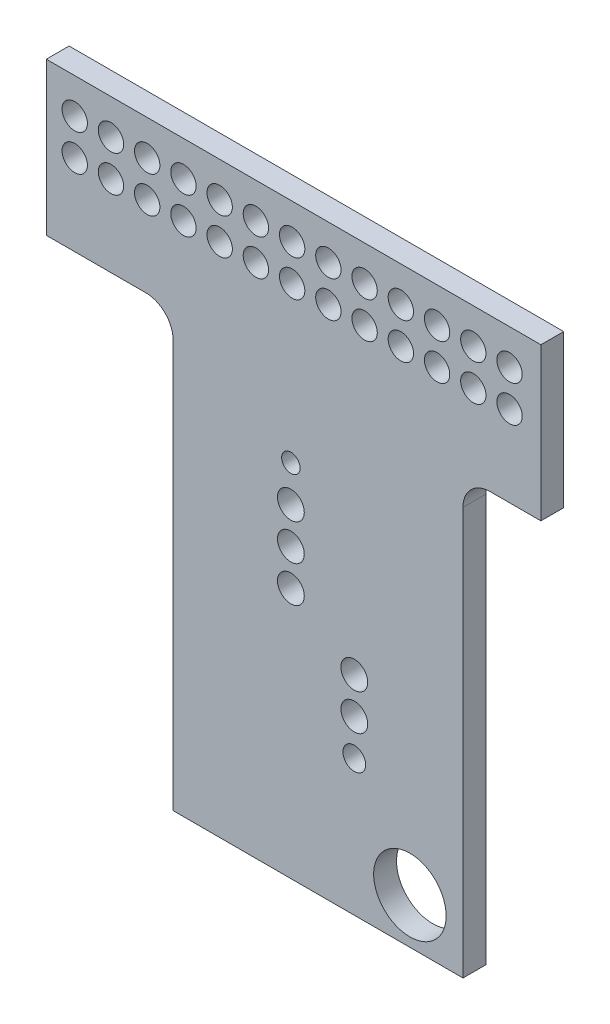
SolidWorks part; units mm, degrees
ref_plane "Front Plane" through (0, 0, 0) normal (0, 0, 1) x (1, 0, 0)
ref_plane "Top Plane" through (0, 0, 0) normal (0, 1, 0) x (1, 0, 0)
ref_plane "Right Plane" through (0, 0, 0) normal (1, 0, 0) x (0, 0, -1)
sketch "Model" plane through (0, 0, 0) normal (0, 0, 1) x (1, 0, 0)
  line L0 (17.145, 24.3014) -> (17.145, 26.1811) construction
  line L1 (21.59, 10.4648) -> (21.59, 8.5852) construction
  line L8 (22.5298, 8.5852) -> (22.5298, 10.4648) construction
  line L9 (22.5298, 10.4648) -> (20.6502, 10.4648) construction
  line L10 (20.6502, 10.4648) -> (20.6502, 8.5852) construction
  line L11 (20.6502, 8.5852) -> (22.5298, 8.5852) construction
  line L12 (22.5298, 8.5852) -> (22.5298, 10.4648) construction
  line L13 (22.5298, 10.4648) -> (20.6502, 10.4648) construction
  line L14 (20.6502, 10.4648) -> (20.6502, 8.5852) construction
  line L15 (20.6502, 8.5852) -> (22.5298, 8.5852) construction
  line L16 (16.2052, 26.1811) -> (16.2052, 24.3014) construction
  line L17 (16.2052, 24.3014) -> (18.0848, 24.3014) construction
  line L18 (18.0848, 24.3014) -> (18.0848, 26.1811) construction
  line L19 (18.0848, 26.1811) -> (16.2052, 26.1811) construction
  line L20 (16.2052, 26.1811) -> (16.2052, 24.3014) construction
  line L21 (16.2052, 24.3014) -> (18.0848, 24.3014) construction
  line L22 (18.0848, 24.3014) -> (18.0848, 26.1811) construction
  line L23 (18.0848, 26.1811) -> (16.2052, 26.1811) construction
  line L24 (8.89, 0) -> (29.21, 0)
  line L25 (34.671, 41.1734) -> (0, 41.1734)
  line L26 (0, 41.1734) -> (0, 30.48)
  line L27 (0, 30.48) -> (6.985, 30.48)
  line L28 (8.89, 28.575) -> (8.89, 0)
  line L29 (29.21, 28.575) -> (29.21, 0)
  line L30 (34.671, 30.48) -> (34.671, 41.1734)
  line L31 (34.671, 30.48) -> (31.115, 30.48)
  circle A0 centre (17.145, 25.2413) radius 0.6465
  circle A1 centre (21.59, 9.525) radius 0.7974
  arc A2 (8.89, 28.575) -> (6.985, 30.48) centre (6.985, 28.575) ccw
  arc A3 (31.115, 30.48) -> (29.21, 28.575) centre (31.115, 28.575) ccw
  circle A4 centre (1.9939, 38.7096) radius 0.127
  circle A5 centre (1.9939, 36.1696) radius 0.127
  circle A6 centre (4.5339, 38.7096) radius 0.127
  circle A7 centre (4.5339, 36.1696) radius 0.127
  circle A8 centre (7.0739, 38.7096) radius 0.127
  circle A9 centre (7.0739, 36.1696) radius 0.127
  circle A10 centre (9.6139, 38.7096) radius 0.127
  circle A11 centre (9.6139, 36.1696) radius 0.127
  circle A12 centre (12.1539, 38.7096) radius 0.127
  circle A13 centre (12.1539, 36.1696) radius 0.127
  circle A14 centre (1.9939, 38.7096) radius 0.889
  circle A15 centre (1.9939, 36.1696) radius 0.889
  circle A16 centre (4.5339, 36.1696) radius 0.889
  circle A17 centre (7.0739, 36.1696) radius 0.889
  circle A18 centre (9.6139, 36.1696) radius 0.889
  circle A19 centre (12.1539, 36.1696) radius 0.889
  circle A20 centre (4.5339, 38.7096) radius 0.889
  circle A21 centre (7.0739, 38.7096) radius 0.889
  circle A22 centre (9.6139, 38.7096) radius 0.889
  circle A23 centre (12.1539, 38.7096) radius 0.889
  circle A24 centre (14.6939, 38.7096) radius 0.127
  circle A25 centre (14.6939, 36.1696) radius 0.127
  circle A26 centre (17.2339, 38.7096) radius 0.127
  circle A27 centre (17.2339, 36.1696) radius 0.127
  circle A28 centre (19.7739, 38.7096) radius 0.127
  circle A29 centre (19.7739, 36.1696) radius 0.127
  circle A30 centre (22.3139, 38.7096) radius 0.127
  circle A31 centre (22.3139, 36.1696) radius 0.127
  circle A32 centre (24.8539, 38.7096) radius 0.127
  circle A33 centre (24.8539, 36.1696) radius 0.127
  circle A34 centre (14.6939, 38.7096) radius 0.889
  circle A35 centre (14.6939, 36.1696) radius 0.889
  circle A36 centre (17.2339, 36.1696) radius 0.889
  circle A37 centre (19.7739, 36.1696) radius 0.889
  circle A38 centre (22.3139, 36.1696) radius 0.889
  circle A39 centre (24.8539, 36.1696) radius 0.889
  circle A40 centre (17.2339, 38.7096) radius 0.889
  circle A41 centre (19.7739, 38.7096) radius 0.889
  circle A42 centre (22.3139, 38.7096) radius 0.889
  circle A43 centre (24.8539, 38.7096) radius 0.889
  circle A44 centre (27.3939, 38.7096) radius 0.127
  circle A45 centre (27.3939, 36.1696) radius 0.127
  circle A46 centre (29.9339, 38.7096) radius 0.127
  circle A47 centre (29.9339, 36.1696) radius 0.127
  circle A48 centre (32.4739, 38.7096) radius 0.127
  circle A49 centre (32.4739, 36.1696) radius 0.127
  circle A50 centre (27.3939, 38.7096) radius 0.889
  circle A51 centre (27.3939, 36.1696) radius 0.889
  circle A52 centre (29.9339, 36.1696) radius 0.889
  circle A53 centre (32.4739, 36.1696) radius 0.889
  circle A54 centre (29.9339, 38.7096) radius 0.889
  circle A55 centre (32.4739, 38.7096) radius 0.889
  circle B0 centre (1.9939, 36.1696) radius 0.6858
  circle B1 centre (1.9939, 36.1696) radius 0.6858
  line B2 (1.3081, 38.4255) -> (1.3081, 38.9937)
  line B3 (1.3081, 38.9937) -> (1.7098, 39.3954)
  line B4 (1.7098, 39.3954) -> (2.278, 39.3954)
  line B5 (2.278, 39.3954) -> (2.6797, 38.9937)
  line B6 (2.6797, 38.9937) -> (2.6797, 38.4255)
  line B7 (2.6797, 38.4255) -> (2.278, 38.0238)
  line B8 (2.278, 38.0238) -> (1.7098, 38.0238)
  line B9 (1.7098, 38.0238) -> (1.3081, 38.4255)
  line B10 (1.3081, 38.4255) -> (1.3081, 38.9937)
  line B11 (1.3081, 38.9937) -> (1.7098, 39.3954)
  line B12 (1.7098, 39.3954) -> (2.278, 39.3954)
  line B13 (2.278, 39.3954) -> (2.6797, 38.9937)
  line B14 (2.6797, 38.9937) -> (2.6797, 38.4255)
  line B15 (2.6797, 38.4255) -> (2.278, 38.0238)
  line B16 (2.278, 38.0238) -> (1.7098, 38.0238)
  line B17 (1.7098, 38.0238) -> (1.3081, 38.4255)
  line B18 (3.8481, 35.8855) -> (3.8481, 36.4537)
  line B19 (3.8481, 36.4537) -> (4.2498, 36.8554)
  line B20 (4.2498, 36.8554) -> (4.818, 36.8554)
  line B21 (4.818, 36.8554) -> (5.2197, 36.4537)
  line B22 (5.2197, 36.4537) -> (5.2197, 35.8855)
  line B23 (5.2197, 35.8855) -> (4.818, 35.4838)
  line B24 (4.818, 35.4838) -> (4.2498, 35.4838)
  line B25 (4.2498, 35.4838) -> (3.8481, 35.8855)
  line B26 (3.8481, 35.8855) -> (3.8481, 36.4537)
  line B27 (3.8481, 36.4537) -> (4.2498, 36.8554)
  line B28 (4.2498, 36.8554) -> (4.818, 36.8554)
  line B29 (4.818, 36.8554) -> (5.2197, 36.4537)
  line B30 (5.2197, 36.4537) -> (5.2197, 35.8855)
  line B31 (5.2197, 35.8855) -> (4.818, 35.4838)
  line B32 (4.818, 35.4838) -> (4.2498, 35.4838)
  line B33 (4.2498, 35.4838) -> (3.8481, 35.8855)
  line B34 (3.8481, 38.4255) -> (3.8481, 38.9937)
  line B35 (3.8481, 38.9937) -> (4.2498, 39.3954)
  line B36 (4.2498, 39.3954) -> (4.818, 39.3954)
  line B37 (4.818, 39.3954) -> (5.2197, 38.9937)
  line B38 (5.2197, 38.9937) -> (5.2197, 38.4255)
  line B39 (5.2197, 38.4255) -> (4.818, 38.0238)
  line B40 (4.818, 38.0238) -> (4.2498, 38.0238)
  line B41 (4.2498, 38.0238) -> (3.8481, 38.4255)
  line B42 (3.8481, 38.4255) -> (3.8481, 38.9937)
  line B43 (3.8481, 38.9937) -> (4.2498, 39.3954)
  line B44 (4.2498, 39.3954) -> (4.818, 39.3954)
  line B45 (4.818, 39.3954) -> (5.2197, 38.9937)
  line B46 (5.2197, 38.9937) -> (5.2197, 38.4255)
  line B47 (5.2197, 38.4255) -> (4.818, 38.0238)
  line B48 (4.818, 38.0238) -> (4.2498, 38.0238)
  line B49 (4.2498, 38.0238) -> (3.8481, 38.4255)
  line B50 (6.3881, 35.8855) -> (6.3881, 36.4537)
  line B51 (6.3881, 36.4537) -> (6.7898, 36.8554)
  line B52 (6.7898, 36.8554) -> (7.358, 36.8554)
  line B53 (7.358, 36.8554) -> (7.7597, 36.4537)
  line B54 (7.7597, 36.4537) -> (7.7597, 35.8855)
  line B55 (7.7597, 35.8855) -> (7.358, 35.4838)
  line B56 (7.358, 35.4838) -> (6.7898, 35.4838)
  line B57 (6.7898, 35.4838) -> (6.3881, 35.8855)
  line B58 (6.3881, 35.8855) -> (6.3881, 36.4537)
  line B59 (6.3881, 36.4537) -> (6.7898, 36.8554)
  line B60 (6.7898, 36.8554) -> (7.358, 36.8554)
  line B61 (7.358, 36.8554) -> (7.7597, 36.4537)
  line B62 (7.7597, 36.4537) -> (7.7597, 35.8855)
  line B63 (7.7597, 35.8855) -> (7.358, 35.4838)
  line B64 (7.358, 35.4838) -> (6.7898, 35.4838)
  line B65 (6.7898, 35.4838) -> (6.3881, 35.8855)
  line B66 (6.3881, 38.4255) -> (6.3881, 38.9937)
  line B67 (6.3881, 38.9937) -> (6.7898, 39.3954)
  line B68 (6.7898, 39.3954) -> (7.358, 39.3954)
  line B69 (7.358, 39.3954) -> (7.7597, 38.9937)
  line B70 (7.7597, 38.9937) -> (7.7597, 38.4255)
  line B71 (7.7597, 38.4255) -> (7.358, 38.0238)
  line B72 (7.358, 38.0238) -> (6.7898, 38.0238)
  line B73 (6.7898, 38.0238) -> (6.3881, 38.4255)
  line B74 (6.3881, 38.4255) -> (6.3881, 38.9937)
  line B75 (6.3881, 38.9937) -> (6.7898, 39.3954)
  line B76 (6.7898, 39.3954) -> (7.358, 39.3954)
  line B77 (7.358, 39.3954) -> (7.7597, 38.9937)
  line B78 (7.7597, 38.9937) -> (7.7597, 38.4255)
  line B79 (7.7597, 38.4255) -> (7.358, 38.0238)
  line B80 (7.358, 38.0238) -> (6.7898, 38.0238)
  line B81 (6.7898, 38.0238) -> (6.3881, 38.4255)
  line B82 (8.9281, 35.8855) -> (8.9281, 36.4537)
  line B83 (8.9281, 36.4537) -> (9.3298, 36.8554)
  line B84 (9.3298, 36.8554) -> (9.898, 36.8554)
  line B85 (9.898, 36.8554) -> (10.2997, 36.4537)
  line B86 (10.2997, 36.4537) -> (10.2997, 35.8855)
  line B87 (10.2997, 35.8855) -> (9.898, 35.4838)
  line B88 (9.898, 35.4838) -> (9.3298, 35.4838)
  line B89 (9.3298, 35.4838) -> (8.9281, 35.8855)
  line B90 (8.9281, 35.8855) -> (8.9281, 36.4537)
  line B91 (8.9281, 36.4537) -> (9.3298, 36.8554)
  line B92 (9.3298, 36.8554) -> (9.898, 36.8554)
  line B93 (9.898, 36.8554) -> (10.2997, 36.4537)
  line B94 (10.2997, 36.4537) -> (10.2997, 35.8855)
  line B95 (10.2997, 35.8855) -> (9.898, 35.4838)
  line B96 (9.898, 35.4838) -> (9.3298, 35.4838)
  line B97 (9.3298, 35.4838) -> (8.9281, 35.8855)
  line B98 (8.9281, 38.4255) -> (8.9281, 38.9937)
  line B99 (8.9281, 38.9937) -> (9.3298, 39.3954)
  line B100 (9.3298, 39.3954) -> (9.898, 39.3954)
  line B101 (9.898, 39.3954) -> (10.2997, 38.9937)
  line B102 (10.2997, 38.9937) -> (10.2997, 38.4255)
  line B103 (10.2997, 38.4255) -> (9.898, 38.0238)
  line B104 (9.898, 38.0238) -> (9.3298, 38.0238)
  line B105 (9.3298, 38.0238) -> (8.9281, 38.4255)
  line B106 (8.9281, 38.4255) -> (8.9281, 38.9937)
  line B107 (8.9281, 38.9937) -> (9.3298, 39.3954)
  line B108 (9.3298, 39.3954) -> (9.898, 39.3954)
  line B109 (9.898, 39.3954) -> (10.2997, 38.9937)
  line B110 (10.2997, 38.9937) -> (10.2997, 38.4255)
  line B111 (10.2997, 38.4255) -> (9.898, 38.0238)
  line B112 (9.898, 38.0238) -> (9.3298, 38.0238)
  line B113 (9.3298, 38.0238) -> (8.9281, 38.4255)
  line B114 (11.4681, 35.8855) -> (11.4681, 36.4537)
  line B115 (11.4681, 36.4537) -> (11.8698, 36.8554)
  line B116 (11.8698, 36.8554) -> (12.438, 36.8554)
  line B117 (12.438, 36.8554) -> (12.8397, 36.4537)
  line B118 (12.8397, 36.4537) -> (12.8397, 35.8855)
  line B119 (12.8397, 35.8855) -> (12.438, 35.4838)
  line B120 (12.438, 35.4838) -> (11.8698, 35.4838)
  line B121 (11.8698, 35.4838) -> (11.4681, 35.8855)
  line B122 (11.4681, 35.8855) -> (11.4681, 36.4537)
  line B123 (11.4681, 36.4537) -> (11.8698, 36.8554)
  line B124 (11.8698, 36.8554) -> (12.438, 36.8554)
  line B125 (12.438, 36.8554) -> (12.8397, 36.4537)
  line B126 (12.8397, 36.4537) -> (12.8397, 35.8855)
  line B127 (12.8397, 35.8855) -> (12.438, 35.4838)
  line B128 (12.438, 35.4838) -> (11.8698, 35.4838)
  line B129 (11.8698, 35.4838) -> (11.4681, 35.8855)
  line B130 (11.4681, 38.4255) -> (11.4681, 38.9937)
  line B131 (11.4681, 38.9937) -> (11.8698, 39.3954)
  line B132 (11.8698, 39.3954) -> (12.438, 39.3954)
  line B133 (12.438, 39.3954) -> (12.8397, 38.9937)
  line B134 (12.8397, 38.9937) -> (12.8397, 38.4255)
  line B135 (12.8397, 38.4255) -> (12.438, 38.0238)
  line B136 (12.438, 38.0238) -> (11.8698, 38.0238)
  line B137 (11.8698, 38.0238) -> (11.4681, 38.4255)
  line B138 (11.4681, 38.4255) -> (11.4681, 38.9937)
  line B139 (11.4681, 38.9937) -> (11.8698, 39.3954)
  line B140 (11.8698, 39.3954) -> (12.438, 39.3954)
  line B141 (12.438, 39.3954) -> (12.8397, 38.9937)
  line B142 (12.8397, 38.9937) -> (12.8397, 38.4255)
  line B143 (12.8397, 38.4255) -> (12.438, 38.0238)
  line B144 (12.438, 38.0238) -> (11.8698, 38.0238)
  line B145 (11.8698, 38.0238) -> (11.4681, 38.4255)
  line B146 (14.0081, 35.8855) -> (14.0081, 36.4537)
  line B147 (14.0081, 36.4537) -> (14.4098, 36.8554)
  line B148 (14.4098, 36.8554) -> (14.978, 36.8554)
  line B149 (14.978, 36.8554) -> (15.3797, 36.4537)
  line B150 (15.3797, 36.4537) -> (15.3797, 35.8855)
  line B151 (15.3797, 35.8855) -> (14.978, 35.4838)
  line B152 (14.978, 35.4838) -> (14.4098, 35.4838)
  line B153 (14.4098, 35.4838) -> (14.0081, 35.8855)
  line B154 (14.0081, 35.8855) -> (14.0081, 36.4537)
  line B155 (14.0081, 36.4537) -> (14.4098, 36.8554)
  line B156 (14.4098, 36.8554) -> (14.978, 36.8554)
  line B157 (14.978, 36.8554) -> (15.3797, 36.4537)
  line B158 (15.3797, 36.4537) -> (15.3797, 35.8855)
  line B159 (15.3797, 35.8855) -> (14.978, 35.4838)
  line B160 (14.978, 35.4838) -> (14.4098, 35.4838)
  line B161 (14.4098, 35.4838) -> (14.0081, 35.8855)
  line B162 (14.0081, 38.4255) -> (14.0081, 38.9937)
  line B163 (14.0081, 38.9937) -> (14.4098, 39.3954)
  line B164 (14.4098, 39.3954) -> (14.978, 39.3954)
  line B165 (14.978, 39.3954) -> (15.3797, 38.9937)
  line B166 (15.3797, 38.9937) -> (15.3797, 38.4255)
  line B167 (15.3797, 38.4255) -> (14.978, 38.0238)
  line B168 (14.978, 38.0238) -> (14.4098, 38.0238)
  line B169 (14.4098, 38.0238) -> (14.0081, 38.4255)
  line B170 (14.0081, 38.4255) -> (14.0081, 38.9937)
  line B171 (14.0081, 38.9937) -> (14.4098, 39.3954)
  line B172 (14.4098, 39.3954) -> (14.978, 39.3954)
  line B173 (14.978, 39.3954) -> (15.3797, 38.9937)
  line B174 (15.3797, 38.9937) -> (15.3797, 38.4255)
  line B175 (15.3797, 38.4255) -> (14.978, 38.0238)
  line B176 (14.978, 38.0238) -> (14.4098, 38.0238)
  line B177 (14.4098, 38.0238) -> (14.0081, 38.4255)
  line B178 (16.5481, 35.8855) -> (16.5481, 36.4537)
  line B179 (16.5481, 36.4537) -> (16.9498, 36.8554)
  line B180 (16.9498, 36.8554) -> (17.518, 36.8554)
  line B181 (17.518, 36.8554) -> (17.9197, 36.4537)
  line B182 (17.9197, 36.4537) -> (17.9197, 35.8855)
  line B183 (17.9197, 35.8855) -> (17.518, 35.4838)
  line B184 (17.518, 35.4838) -> (16.9498, 35.4838)
  line B185 (16.9498, 35.4838) -> (16.5481, 35.8855)
  line B186 (16.5481, 35.8855) -> (16.5481, 36.4537)
  line B187 (16.5481, 36.4537) -> (16.9498, 36.8554)
  line B188 (16.9498, 36.8554) -> (17.518, 36.8554)
  line B189 (17.518, 36.8554) -> (17.9197, 36.4537)
  line B190 (17.9197, 36.4537) -> (17.9197, 35.8855)
  line B191 (17.9197, 35.8855) -> (17.518, 35.4838)
  line B192 (17.518, 35.4838) -> (16.9498, 35.4838)
  line B193 (16.9498, 35.4838) -> (16.5481, 35.8855)
  line B194 (16.5481, 38.4255) -> (16.5481, 38.9937)
  line B195 (16.5481, 38.9937) -> (16.9498, 39.3954)
  line B196 (16.9498, 39.3954) -> (17.518, 39.3954)
  line B197 (17.518, 39.3954) -> (17.9197, 38.9937)
  line B198 (17.9197, 38.9937) -> (17.9197, 38.4255)
  line B199 (17.9197, 38.4255) -> (17.518, 38.0238)
  line B200 (17.518, 38.0238) -> (16.9498, 38.0238)
  line B201 (16.9498, 38.0238) -> (16.5481, 38.4255)
  line B202 (16.5481, 38.4255) -> (16.5481, 38.9937)
  line B203 (16.5481, 38.9937) -> (16.9498, 39.3954)
  line B204 (16.9498, 39.3954) -> (17.518, 39.3954)
  line B205 (17.518, 39.3954) -> (17.9197, 38.9937)
  line B206 (17.9197, 38.9937) -> (17.9197, 38.4255)
  line B207 (17.9197, 38.4255) -> (17.518, 38.0238)
  line B208 (17.518, 38.0238) -> (16.9498, 38.0238)
  line B209 (16.9498, 38.0238) -> (16.5481, 38.4255)
  line B210 (19.0881, 35.8855) -> (19.0881, 36.4537)
  line B211 (19.0881, 36.4537) -> (19.4898, 36.8554)
  line B212 (19.4898, 36.8554) -> (20.058, 36.8554)
  line B213 (20.058, 36.8554) -> (20.4597, 36.4537)
  line B214 (20.4597, 36.4537) -> (20.4597, 35.8855)
  line B215 (20.4597, 35.8855) -> (20.058, 35.4838)
  line B216 (20.058, 35.4838) -> (19.4898, 35.4838)
  line B217 (19.4898, 35.4838) -> (19.0881, 35.8855)
  line B218 (19.0881, 35.8855) -> (19.0881, 36.4537)
  line B219 (19.0881, 36.4537) -> (19.4898, 36.8554)
  line B220 (19.4898, 36.8554) -> (20.058, 36.8554)
  line B221 (20.058, 36.8554) -> (20.4597, 36.4537)
  line B222 (20.4597, 36.4537) -> (20.4597, 35.8855)
  line B223 (20.4597, 35.8855) -> (20.058, 35.4838)
  line B224 (20.058, 35.4838) -> (19.4898, 35.4838)
  line B225 (19.4898, 35.4838) -> (19.0881, 35.8855)
  line B226 (19.0881, 38.4255) -> (19.0881, 38.9937)
  line B227 (19.0881, 38.9937) -> (19.4898, 39.3954)
  line B228 (19.4898, 39.3954) -> (20.058, 39.3954)
  line B229 (20.058, 39.3954) -> (20.4597, 38.9937)
  line B230 (20.4597, 38.9937) -> (20.4597, 38.4255)
  line B231 (20.4597, 38.4255) -> (20.058, 38.0238)
  line B232 (20.058, 38.0238) -> (19.4898, 38.0238)
  line B233 (19.4898, 38.0238) -> (19.0881, 38.4255)
  line B234 (19.0881, 38.4255) -> (19.0881, 38.9937)
  line B235 (19.0881, 38.9937) -> (19.4898, 39.3954)
  line B236 (19.4898, 39.3954) -> (20.058, 39.3954)
  line B237 (20.058, 39.3954) -> (20.4597, 38.9937)
  line B238 (20.4597, 38.9937) -> (20.4597, 38.4255)
  line B239 (20.4597, 38.4255) -> (20.058, 38.0238)
  line B240 (20.058, 38.0238) -> (19.4898, 38.0238)
  line B241 (19.4898, 38.0238) -> (19.0881, 38.4255)
  line B242 (21.6281, 35.8855) -> (21.6281, 36.4537)
  line B243 (21.6281, 36.4537) -> (22.0298, 36.8554)
  line B244 (22.0298, 36.8554) -> (22.598, 36.8554)
  line B245 (22.598, 36.8554) -> (22.9997, 36.4537)
  line B246 (22.9997, 36.4537) -> (22.9997, 35.8855)
  line B247 (22.9997, 35.8855) -> (22.598, 35.4838)
  line B248 (22.598, 35.4838) -> (22.0298, 35.4838)
  line B249 (22.0298, 35.4838) -> (21.6281, 35.8855)
  line B250 (21.6281, 35.8855) -> (21.6281, 36.4537)
  line B251 (21.6281, 36.4537) -> (22.0298, 36.8554)
  line B252 (22.0298, 36.8554) -> (22.598, 36.8554)
  line B253 (22.598, 36.8554) -> (22.9997, 36.4537)
  line B254 (22.9997, 36.4537) -> (22.9997, 35.8855)
  line B255 (22.9997, 35.8855) -> (22.598, 35.4838)
  line B256 (22.598, 35.4838) -> (22.0298, 35.4838)
  line B257 (22.0298, 35.4838) -> (21.6281, 35.8855)
  line B258 (21.6281, 38.4255) -> (21.6281, 38.9937)
  line B259 (21.6281, 38.9937) -> (22.0298, 39.3954)
  line B260 (22.0298, 39.3954) -> (22.598, 39.3954)
  line B261 (22.598, 39.3954) -> (22.9997, 38.9937)
  line B262 (22.9997, 38.9937) -> (22.9997, 38.4255)
  line B263 (22.9997, 38.4255) -> (22.598, 38.0238)
  line B264 (22.598, 38.0238) -> (22.0298, 38.0238)
  line B265 (22.0298, 38.0238) -> (21.6281, 38.4255)
  line B266 (21.6281, 38.4255) -> (21.6281, 38.9937)
  line B267 (21.6281, 38.9937) -> (22.0298, 39.3954)
  line B268 (22.0298, 39.3954) -> (22.598, 39.3954)
  line B269 (22.598, 39.3954) -> (22.9997, 38.9937)
  line B270 (22.9997, 38.9937) -> (22.9997, 38.4255)
  line B271 (22.9997, 38.4255) -> (22.598, 38.0238)
  line B272 (22.598, 38.0238) -> (22.0298, 38.0238)
  line B273 (22.0298, 38.0238) -> (21.6281, 38.4255)
  line B274 (24.1681, 35.8855) -> (24.1681, 36.4537)
  line B275 (24.1681, 36.4537) -> (24.5698, 36.8554)
  line B276 (24.5698, 36.8554) -> (25.138, 36.8554)
  line B277 (25.138, 36.8554) -> (25.5397, 36.4537)
  line B278 (25.5397, 36.4537) -> (25.5397, 35.8855)
  line B279 (25.5397, 35.8855) -> (25.138, 35.4838)
  line B280 (25.138, 35.4838) -> (24.5698, 35.4838)
  line B281 (24.5698, 35.4838) -> (24.1681, 35.8855)
  line B282 (24.1681, 35.8855) -> (24.1681, 36.4537)
  line B283 (24.1681, 36.4537) -> (24.5698, 36.8554)
  line B284 (24.5698, 36.8554) -> (25.138, 36.8554)
  line B285 (25.138, 36.8554) -> (25.5397, 36.4537)
  line B286 (25.5397, 36.4537) -> (25.5397, 35.8855)
  line B287 (25.5397, 35.8855) -> (25.138, 35.4838)
  line B288 (25.138, 35.4838) -> (24.5698, 35.4838)
  line B289 (24.5698, 35.4838) -> (24.1681, 35.8855)
  line B290 (24.1681, 38.4255) -> (24.1681, 38.9937)
  line B291 (24.1681, 38.9937) -> (24.5698, 39.3954)
  line B292 (24.5698, 39.3954) -> (25.138, 39.3954)
  line B293 (25.138, 39.3954) -> (25.5397, 38.9937)
  line B294 (25.5397, 38.9937) -> (25.5397, 38.4255)
  line B295 (25.5397, 38.4255) -> (25.138, 38.0238)
  line B296 (25.138, 38.0238) -> (24.5698, 38.0238)
  line B297 (24.5698, 38.0238) -> (24.1681, 38.4255)
  line B298 (24.1681, 38.4255) -> (24.1681, 38.9937)
  line B299 (24.1681, 38.9937) -> (24.5698, 39.3954)
  line B300 (24.5698, 39.3954) -> (25.138, 39.3954)
  line B301 (25.138, 39.3954) -> (25.5397, 38.9937)
  line B302 (25.5397, 38.9937) -> (25.5397, 38.4255)
  line B303 (25.5397, 38.4255) -> (25.138, 38.0238)
  line B304 (25.138, 38.0238) -> (24.5698, 38.0238)
  line B305 (24.5698, 38.0238) -> (24.1681, 38.4255)
  line B306 (26.7081, 35.8855) -> (26.7081, 36.4537)
  line B307 (26.7081, 36.4537) -> (27.1098, 36.8554)
  line B308 (27.1098, 36.8554) -> (27.678, 36.8554)
  line B309 (27.678, 36.8554) -> (28.0797, 36.4537)
  line B310 (28.0797, 36.4537) -> (28.0797, 35.8855)
  line B311 (28.0797, 35.8855) -> (27.678, 35.4838)
  line B312 (27.678, 35.4838) -> (27.1098, 35.4838)
  line B313 (27.1098, 35.4838) -> (26.7081, 35.8855)
  line B314 (26.7081, 35.8855) -> (26.7081, 36.4537)
  line B315 (26.7081, 36.4537) -> (27.1098, 36.8554)
  line B316 (27.1098, 36.8554) -> (27.678, 36.8554)
  line B317 (27.678, 36.8554) -> (28.0797, 36.4537)
  line B318 (28.0797, 36.4537) -> (28.0797, 35.8855)
  line B319 (28.0797, 35.8855) -> (27.678, 35.4838)
  line B320 (27.678, 35.4838) -> (27.1098, 35.4838)
  line B321 (27.1098, 35.4838) -> (26.7081, 35.8855)
  line B322 (26.7081, 38.4255) -> (26.7081, 38.9937)
  line B323 (26.7081, 38.9937) -> (27.1098, 39.3954)
  line B324 (27.1098, 39.3954) -> (27.678, 39.3954)
  line B325 (27.678, 39.3954) -> (28.0797, 38.9937)
  line B326 (28.0797, 38.9937) -> (28.0797, 38.4255)
  line B327 (28.0797, 38.4255) -> (27.678, 38.0238)
  line B328 (27.678, 38.0238) -> (27.1098, 38.0238)
  line B329 (27.1098, 38.0238) -> (26.7081, 38.4255)
  line B330 (26.7081, 38.4255) -> (26.7081, 38.9937)
  line B331 (26.7081, 38.9937) -> (27.1098, 39.3954)
  line B332 (27.1098, 39.3954) -> (27.678, 39.3954)
  line B333 (27.678, 39.3954) -> (28.0797, 38.9937)
  line B334 (28.0797, 38.9937) -> (28.0797, 38.4255)
  line B335 (28.0797, 38.4255) -> (27.678, 38.0238)
  line B336 (27.678, 38.0238) -> (27.1098, 38.0238)
  line B337 (27.1098, 38.0238) -> (26.7081, 38.4255)
  line B338 (29.2481, 35.8855) -> (29.2481, 36.4537)
  line B339 (29.2481, 36.4537) -> (29.6498, 36.8554)
  line B340 (29.6498, 36.8554) -> (30.218, 36.8554)
  line B341 (30.218, 36.8554) -> (30.6197, 36.4537)
  line B342 (30.6197, 36.4537) -> (30.6197, 35.8855)
  line B343 (30.6197, 35.8855) -> (30.218, 35.4838)
  line B344 (30.218, 35.4838) -> (29.6498, 35.4838)
  line B345 (29.6498, 35.4838) -> (29.2481, 35.8855)
  line B346 (29.2481, 35.8855) -> (29.2481, 36.4537)
  line B347 (29.2481, 36.4537) -> (29.6498, 36.8554)
  line B348 (29.6498, 36.8554) -> (30.218, 36.8554)
  line B349 (30.218, 36.8554) -> (30.6197, 36.4537)
  line B350 (30.6197, 36.4537) -> (30.6197, 35.8855)
  line B351 (30.6197, 35.8855) -> (30.218, 35.4838)
  line B352 (30.218, 35.4838) -> (29.6498, 35.4838)
  line B353 (29.6498, 35.4838) -> (29.2481, 35.8855)
  line B354 (29.2481, 38.4255) -> (29.2481, 38.9937)
  line B355 (29.2481, 38.9937) -> (29.6498, 39.3954)
  line B356 (29.6498, 39.3954) -> (30.218, 39.3954)
  line B357 (30.218, 39.3954) -> (30.6197, 38.9937)
  line B358 (30.6197, 38.9937) -> (30.6197, 38.4255)
  line B359 (30.6197, 38.4255) -> (30.218, 38.0238)
  line B360 (30.218, 38.0238) -> (29.6498, 38.0238)
  line B361 (29.6498, 38.0238) -> (29.2481, 38.4255)
  line B362 (29.2481, 38.4255) -> (29.2481, 38.9937)
  line B363 (29.2481, 38.9937) -> (29.6498, 39.3954)
  line B364 (29.6498, 39.3954) -> (30.218, 39.3954)
  line B365 (30.218, 39.3954) -> (30.6197, 38.9937)
  line B366 (30.6197, 38.9937) -> (30.6197, 38.4255)
  line B367 (30.6197, 38.4255) -> (30.218, 38.0238)
  line B368 (30.218, 38.0238) -> (29.6498, 38.0238)
  line B369 (29.6498, 38.0238) -> (29.2481, 38.4255)
  line B370 (31.7881, 35.8855) -> (31.7881, 36.4537)
  line B371 (31.7881, 36.4537) -> (32.1898, 36.8554)
  line B372 (32.1898, 36.8554) -> (32.758, 36.8554)
  line B373 (32.758, 36.8554) -> (33.1597, 36.4537)
  line B374 (33.1597, 36.4537) -> (33.1597, 35.8855)
  line B375 (33.1597, 35.8855) -> (32.758, 35.4838)
  line B376 (32.758, 35.4838) -> (32.1898, 35.4838)
  line B377 (32.1898, 35.4838) -> (31.7881, 35.8855)
  line B378 (31.7881, 35.8855) -> (31.7881, 36.4537)
  line B379 (31.7881, 36.4537) -> (32.1898, 36.8554)
  line B380 (32.1898, 36.8554) -> (32.758, 36.8554)
  line B381 (32.758, 36.8554) -> (33.1597, 36.4537)
  line B382 (33.1597, 36.4537) -> (33.1597, 35.8855)
  line B383 (33.1597, 35.8855) -> (32.758, 35.4838)
  line B384 (32.758, 35.4838) -> (32.1898, 35.4838)
  line B385 (32.1898, 35.4838) -> (31.7881, 35.8855)
  line B386 (31.7881, 38.4255) -> (31.7881, 38.9937)
  line B387 (31.7881, 38.9937) -> (32.1898, 39.3954)
  line B388 (32.1898, 39.3954) -> (32.758, 39.3954)
  line B389 (32.758, 39.3954) -> (33.1597, 38.9937)
  line B390 (33.1597, 38.9937) -> (33.1597, 38.4255)
  line B391 (33.1597, 38.4255) -> (32.758, 38.0238)
  line B392 (32.758, 38.0238) -> (32.1898, 38.0238)
  line B393 (32.1898, 38.0238) -> (31.7881, 38.4255)
  line B394 (31.7881, 38.4255) -> (31.7881, 38.9937)
  line B395 (31.7881, 38.9937) -> (32.1898, 39.3954)
  line B396 (32.1898, 39.3954) -> (32.758, 39.3954)
  line B397 (32.758, 39.3954) -> (33.1597, 38.9937)
  line B398 (33.1597, 38.9937) -> (33.1597, 38.4255)
  line B399 (33.1597, 38.4255) -> (32.758, 38.0238)
  line B400 (32.758, 38.0238) -> (32.1898, 38.0238)
  line B401 (32.1898, 38.0238) -> (31.7881, 38.4255)
  circle B402 centre (21.59, 12.065) radius 0.9398
  circle B403 centre (21.59, 12.065) radius 0.9398
  circle B404 centre (21.59, 14.605) radius 0.9398
  circle B405 centre (21.59, 14.605) radius 0.9398
  circle B406 centre (17.145, 22.7012) radius 0.9398
  circle B407 centre (17.145, 22.7012) radius 0.9398
  circle B408 centre (17.145, 20.1612) radius 0.9398
  circle B409 centre (17.145, 20.1612) radius 0.9398
  circle B410 centre (17.145, 17.6212) radius 0.9398
  circle B411 centre (17.145, 17.6212) radius 0.9398
  circle B412 centre (25.4889, 3.175) radius 2.54
  circle B413 centre (25.4889, 3.175) radius 2.54
sketch_block_instance "ROUNDP-1"
sketch_block "ROUNDP"
sketch_block_instance "ROUNDP-2"
sketch_block_instance "OCTAGONP-1"
sketch_block "OCTAGONP"
sketch_block_instance "OCTAGONP-2"
sketch_block_instance "OCTAGONP-3"
sketch_block_instance "OCTAGONP-4"
sketch_block_instance "OCTAGONP-5"
sketch_block_instance "OCTAGONP-6"
sketch_block_instance "OCTAGONP-7"
sketch_block_instance "OCTAGONP-8"
sketch_block_instance "OCTAGONP-9"
sketch_block_instance "OCTAGONP-10"
sketch_block_instance "OCTAGONP-11"
sketch_block_instance "OCTAGONP-12"
sketch_block_instance "OCTAGONP-13"
sketch_block_instance "OCTAGONP-14"
sketch_block_instance "OCTAGONP-15"
sketch_block_instance "OCTAGONP-16"
sketch_block_instance "OCTAGONP-17"
sketch_block_instance "OCTAGONP-18"
sketch_block_instance "OCTAGONP-19"
sketch_block_instance "OCTAGONP-20"
sketch_block_instance "OCTAGONP-21"
sketch_block_instance "OCTAGONP-22"
sketch_block_instance "OCTAGONP-23"
sketch_block_instance "OCTAGONP-24"
sketch_block_instance "OCTAGONP-25"
sketch_block_instance "OCTAGONP-26"
sketch_block_instance "OCTAGONP-27"
sketch_block_instance "OCTAGONP-28"
sketch_block_instance "OCTAGONP-29"
sketch_block_instance "OCTAGONP-30"
sketch_block_instance "OCTAGONP-31"
sketch_block_instance "OCTAGONP-32"
sketch_block_instance "OCTAGONP-33"
sketch_block_instance "OCTAGONP-34"
sketch_block_instance "OCTAGONP-35"
sketch_block_instance "OCTAGONP-36"
sketch_block_instance "OCTAGONP-37"
sketch_block_instance "OCTAGONP-38"
sketch_block_instance "OCTAGONP-39"
sketch_block_instance "OCTAGONP-40"
sketch_block_instance "OCTAGONP-41"
sketch_block_instance "OCTAGONP-42"
sketch_block_instance "OCTAGONP-43"
sketch_block_instance "OCTAGONP-44"
sketch_block_instance "OCTAGONP-45"
sketch_block_instance "OCTAGONP-46"
sketch_block_instance "OCTAGONP-47"
sketch_block_instance "OCTAGONP-48"
sketch_block_instance "OCTAGONP-49"
sketch_block_instance "OCTAGONP-50"
sketch_block_instance "ROUNDP-3"
sketch_block_instance "ROUNDP-4"
sketch_block_instance "ROUNDP-5"
sketch_block_instance "ROUNDP-6"
sketch_block_instance "ROUNDP-7"
sketch_block_instance "ROUNDP-8"
sketch_block_instance "ROUNDP-9"
sketch_block_instance "ROUNDP-10"
sketch_block_instance "ROUNDP-11"
sketch_block_instance "ROUNDP-12"
sketch_block_instance "ROUNDV-1"
sketch_block "ROUNDV"
sketch_block_instance "ROUNDV-2"
extrude "Boss-Extrude1" add sketch "Model" along normal blind 1.6002 contours A3 L31 L30 L25 L26 L27 A2 L28 L24 L29 B412 B410 B408 B406 B404 B402 A55 A54 A53 A52 A51 A50 A43 A42 A41 A40 A39 A38 A37 A36
